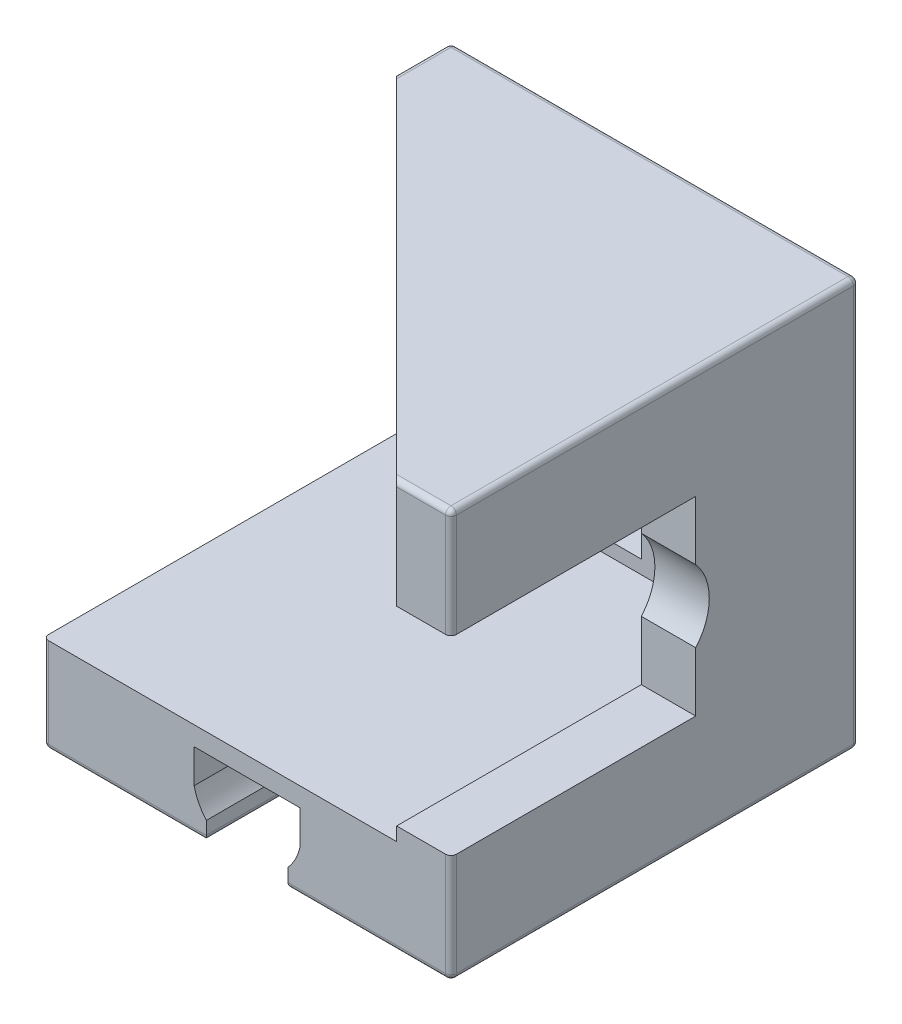
SolidWorks part; units mm, degrees
ref_plane "前视基准面" through (0, 0, 0) normal (0, 0, 1) x (1, 0, 0)
ref_plane "上视基准面" through (0, 0, 0) normal (0, 1, 0) x (1, 0, 0)
ref_plane "右视基准面" through (0, 0, 0) normal (1, 0, 0) x (0, 0, -1)
sketch "草图1" plane through (0, 0, 0) normal (0, 0, 1) x (1, 0, 0)
  line L1 (-7.5, 0) -> (7.5, 0)
  line L2 (-7.5, 0) -> (-7.5, 15)
  line L3 (-7.5, 15) -> (7.5, 15)
  line L4 (7.5, 0) -> (7.5, 15)
extrude "凸台-拉伸1" add sketch "草图1" against normal blind 15
sketch "草图2" plane through (-7.5, 0, 0) normal (-1, 0, 0) x (0, 0, 1)
  line L0 (0, 15) -> (0, 0) construction
  line L1 (-13, 3.5) -> (0, 3.5)
  line L2 (-13, 3.5) -> (-13, 13)
  line L3 (-13, 13) -> (0, 13)
  line L4 (0, 3.5) -> (0, 13)
extrude "切除-拉伸1" cut sketch "草图2" against normal blind 13
sketch "草图3" plane through (0, 0, 0) normal (0, 0, 1) x (1, 0, 0)
  line L0 (-1.5, 0) -> (-1.5, 0.6771)
  line L1 (-7.5, 0) -> (7.5, 0) construction
  line L2 (1.5, 0) -> (1.5, 0.6771)
  line L3 (-1.95, 2.8) -> (1.95, 2.8)
  line L4 (-1.95, 2.8) -> (-1.95, 1.5556)
  line L5 (1.95, 2.8) -> (1.95, 1.5556)
  line L6 (-1.5, 0) -> (1.5, 0)
  arc A0 (1.5, 0.6771) -> (1.95, 1.5556) centre (0, 2) ccw
  arc A1 (-1.95, 1.5556) -> (-1.5, 0.6771) centre (0, 2) ccw
extrude "切除-拉伸2" cut sketch "草图3" against normal blind 9.45
sketch "草图4" plane through (0, 0, 0) normal (0, 0, 1) x (1, 0, 0)
  line L2 (-1.5, 15.6771) -> (1.5, 15.6771)
  line L5 (-1.95, 17.5) -> (1.95, 17.5)
  line L6 (-1.95, 17.5) -> (-1.95, 16.5556)
  line L7 (1.95, 17.5) -> (1.95, 16.5556)
  arc A1 (-1.95, 16.5556) -> (-1.5, 15.6771) centre (0, 17) ccw
  arc A2 (1.5, 15.6771) -> (1.95, 16.5556) centre (0, 17) ccw
extrude "凸台-拉伸2" add sketch "草图4" against normal blind 6 from offset 4.5 offset against normal yes
sketch "草图5" plane through (0, 15, 0) normal (0, 1, 0) x (-1, 0, 0)
  line L1 (1.5, -9) -> (-1.5, -9)
  line L2 (1.5, -9) -> (1.5, -6)
  line L3 (1.5, -6) -> (-1.5, -6)
  line L4 (-1.5, -9) -> (-1.5, -6)
extrude "凸台-拉伸3" add sketch "草图5" along normal blind 1
sketch "草图6" plane through (0, 0, -15) normal (0, 0, -1) x (-1, 0, 0)
  line L0 (-1.5, 6.1771) -> (-1.5, 4)
  line L1 (-1.5, 11) -> (1.5, 11)
  line L2 (-1.5, 11) -> (-1.5, 8.8229)
  line L3 (-1.5, 4) -> (1.5, 4)
  line L4 (1.5, 11) -> (1.5, 8.8229)
  line L5 (1.5, 6.1771) -> (1.5, 4)
  arc A0 (-1.5, 8.8229) -> (-1.5, 6.1771) centre (0, 7.5) ccw
  arc A1 (1.5, 6.1771) -> (1.5, 8.8229) centre (0, 7.5) ccw
extrude "切除-拉伸3" cut sketch "草图6" against normal up to next
sketch "草图7" plane through (7.5, 0, 0) normal (1, 0, 0) x (0, 0, -1)
  line L0 (6, 6.1771) -> (6, 4)
  line L1 (6, 11) -> (9, 11)
  line L2 (6, 11) -> (6, 8.8229)
  line L3 (6, 4) -> (9, 4)
  line L4 (9, 11) -> (9, 8.8229)
  line L5 (9, 6.1771) -> (9, 4)
  arc A0 (6, 8.8229) -> (6, 6.1771) centre (7.5, 7.5) ccw
  arc A1 (9, 6.1771) -> (9, 8.8229) centre (7.5, 7.5) ccw
extrude "切除-拉伸4" cut sketch "草图7" against normal up to next
sketch "草图8" plane through (0, 0, 0) normal (1, 0, 0) x (0, 0, -1)
  line L2 (5.55, 17.5) -> (5.55, 16.5556)
  line L3 (7.5, 18.1799) -> (7.5, 15.0835) construction
  line L4 (6, 15.6771) -> (4.5, 15.6771)
  line L7 (6, 15.6771) -> (4.5, 15.6771) construction
  line L8 (4.5, 15.6771) -> (4.5, 17.5)
  line L9 (4.5, 17.5) -> (5.55, 17.5)
  line L10 (10.5, 17.5) -> (9.45, 17.5)
  line L11 (10.5, 15.6771) -> (10.5, 17.5)
  line L12 (9, 15.6771) -> (10.5, 15.6771)
  line L13 (9.45, 17.5) -> (9.45, 16.5556)
  arc A0 (5.55, 16.5556) -> (6, 15.6771) centre (7.5, 17) ccw
  arc A1 (9.45, 16.5556) -> (9, 15.6771) centre (7.5, 17) cw
extrude "切除-拉伸5" cut sketch "草图8" against normal up to next and the other way up to next
sketch "草图10" plane through (0, 0, 0) normal (0, 0, 1) x (1, 0, 0)
  line L0 (7.5, 15) -> (-7.5, 15) construction
  line L1 (-2.8836, 15) -> (2.8836, 15)
  line L2 (-2.8836, 15) -> (-2.8836, 17.8581)
  line L3 (-2.8836, 17.8581) -> (2.8836, 17.8581)
  line L4 (2.8836, 15) -> (2.8836, 17.8581)
extrude "切除-拉伸7" cut sketch "草图10" against normal through all
sketch "草图11" plane through (0, 15, 0) normal (0, 1, 0) x (-1, 0, 0)
  line L0 (7.5, -13) -> (7.5, 0)
  line L1 (7.5, -15) -> (7.5, 0) construction
  line L2 (7.5, -13) -> (-5.5, 0)
  line L5 (7.5, 0) -> (-5.5, 0)
extrude "切除-拉伸8" cut sketch "草图11" against normal up to surface (2 mm away) up to face at (-1, 13, -6.5)
fillet "圆角2" radius 0.2 16 edges at (4.5, 0, 0) (7.5, 0, -7.5) (0, 0, -15) (-7.5, 0, -7.5) (-4.5, 0, 0) (-1.5, 0, -4.725) (0, 0, -9.45) (1.5, 0, -4.725) (7.5, 7.5, -15) (0, 15, -15) (-7.5, 15, -14) (-7.5, 7.5, -15) (-7.5, 1.75, 0) (7.5, 7.5, 0) (7.5, 15, -7.5) (6.5, 15, 0)
sketch "草图12" plane through (5.5, 0, 0) normal (-1, 0, 0) x (0, 0, 1)
  line L0 (0, 3.5) -> (0, 13) construction
  line L1 (-9, 11) -> (0, 11)
  line L2 (-9, 11) -> (-9, 4)
  line L3 (-9, 4) -> (0, 4)
  line L4 (0, 11) -> (0, 4)
extrude "切除-拉伸9" cut sketch "草图12" against normal up to next
sketch "草图13" plane through (0, 0, -13) normal (0, 0, 1) x (1, 0, 0)
  line L0 (-7.5, 13) -> (-7.5, 3.5) construction
  line L1 (1.5, 11) -> (-7.5, 11)
  line L2 (1.5, 11) -> (1.5, 4)
  line L3 (1.5, 4) -> (-7.5, 4)
  line L4 (-7.5, 11) -> (-7.5, 4)
extrude "切除-拉伸10" cut sketch "草图13" against normal up to next
